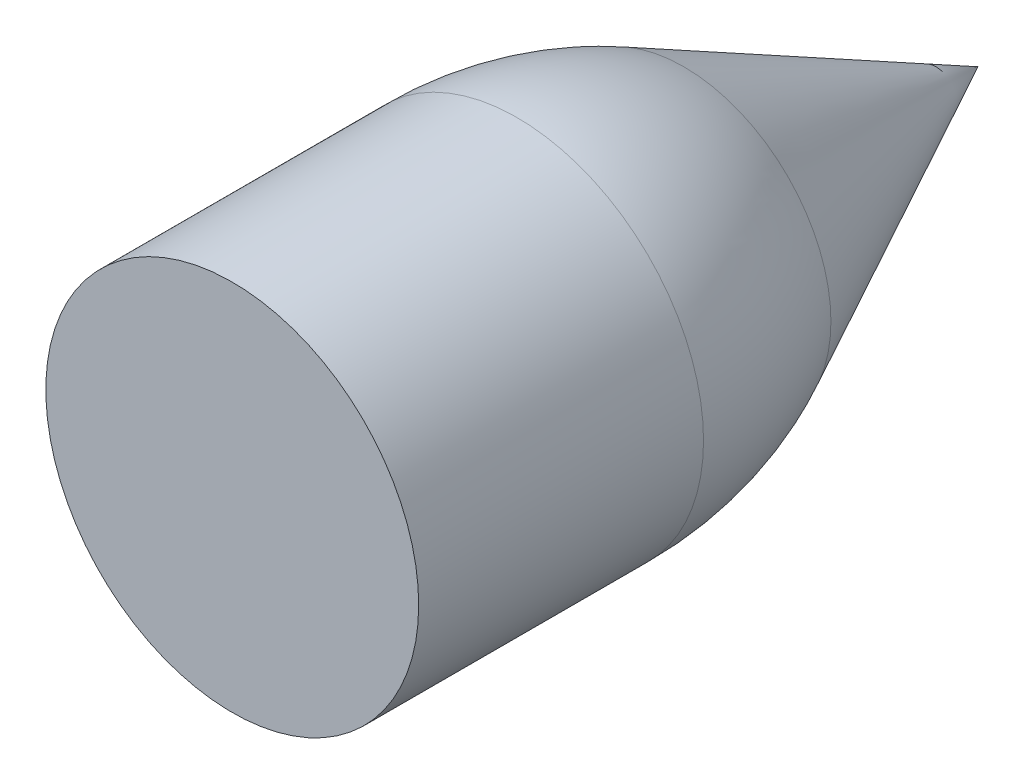
SolidWorks part; units mm, degrees
ref_plane "Ön Düzlem" through (0, 0, 0) normal (0, 0, 1) x (1, 0, 0)
ref_plane "Üst Düzlem" through (0, 0, 0) normal (0, 1, 0) x (1, 0, 0)
ref_plane "Sağ Düzlem" through (0, 0, 0) normal (1, 0, 0) x (0, 0, -1)
sketch "Sketch2" plane through (0, 0, 0) normal (1, 0, 0) x (0, 0, -1)
  line L0 (0, 0) -> (20, 0)
  line L1 (0, -5) -> (7.6393, -5)
  line L2 (12.1115, -3.9443) -> (20, 0)
  line L3 (0, -5) -> (20, -5) construction
  line L4 (0, 0) -> (0, -5)
  arc A0 (12.1115, -3.9443) -> (7.6393, -5) centre (7.6393, 5) cw
  dimension "D2" = 10
  dimension "D1" = 5
revolve "Revolve1" add sketch "Sketch2" angle 360 about L0
